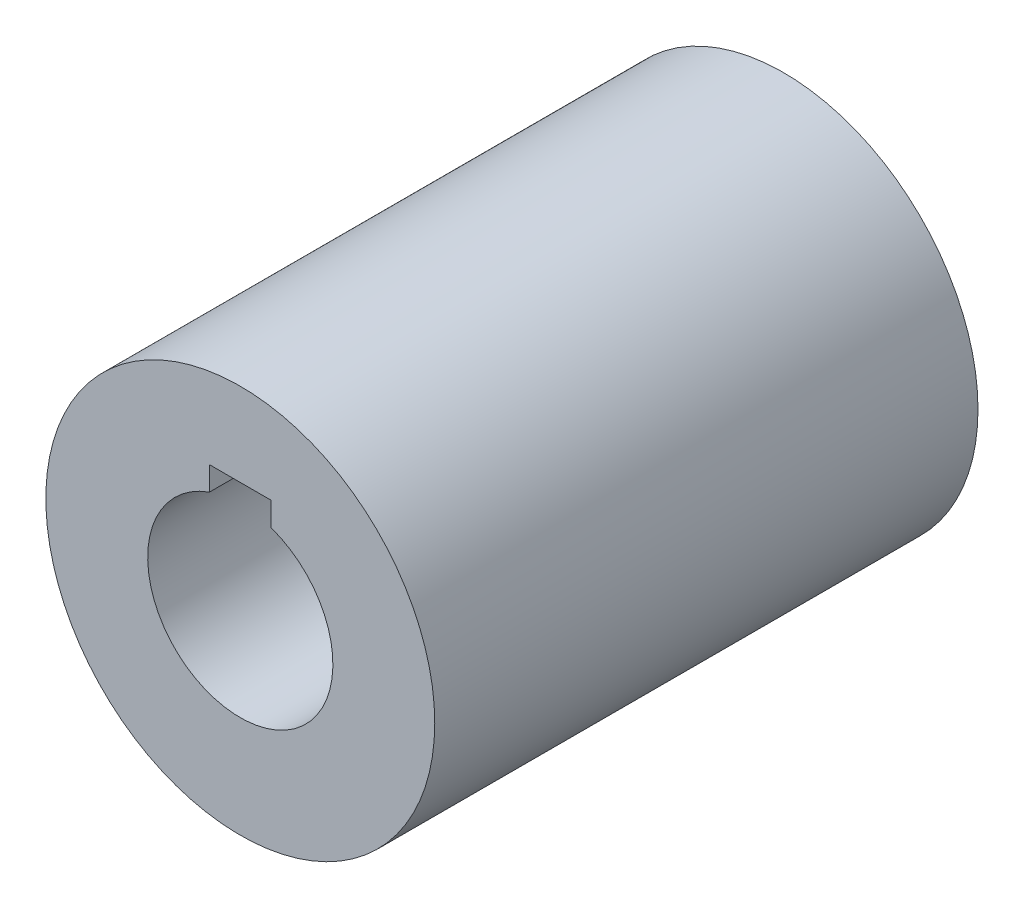
SolidWorks part; units mm, degrees
material "Stainless Steel (ferritic)"
ref_plane "Front Plane" through (0, 0, 0) normal (0, 0, 1) x (1, 0, 0)
ref_plane "Top Plane" through (0, 0, 0) normal (0, 1, 0) x (1, 0, 0)
ref_plane "Right Plane" through (0, 0, 0) normal (1, 0, 0) x (0, 0, -1)
sketch "Sketch1" plane through (0, 0, 0) normal (0, 0, 1) x (1, 0, 0)
  line L0 (-5, 18) -> (5, 18)
  line L2 (-5, 18) -> (-5, 14.1421)
  line L3 (5, 18) -> (5, 14.1421)
  arc A1 (-5, 14.1421) -> (5, 14.1421) centre (0, 0) ccw
  circle A2 centre (0, 0) radius 31.5
  point P3 (0, -15)
  point P6 (0, 18)
  point P7 (8.9993, 18.6193)
  point P8 (0, 0)
  dimension "D1" = 30
  dimension "D3" = 63
  dimension "D2" = 10
  dimension "D4" = 33
extrude "Boss-Extrude1" add sketch "Sketch1" along normal blind 88
